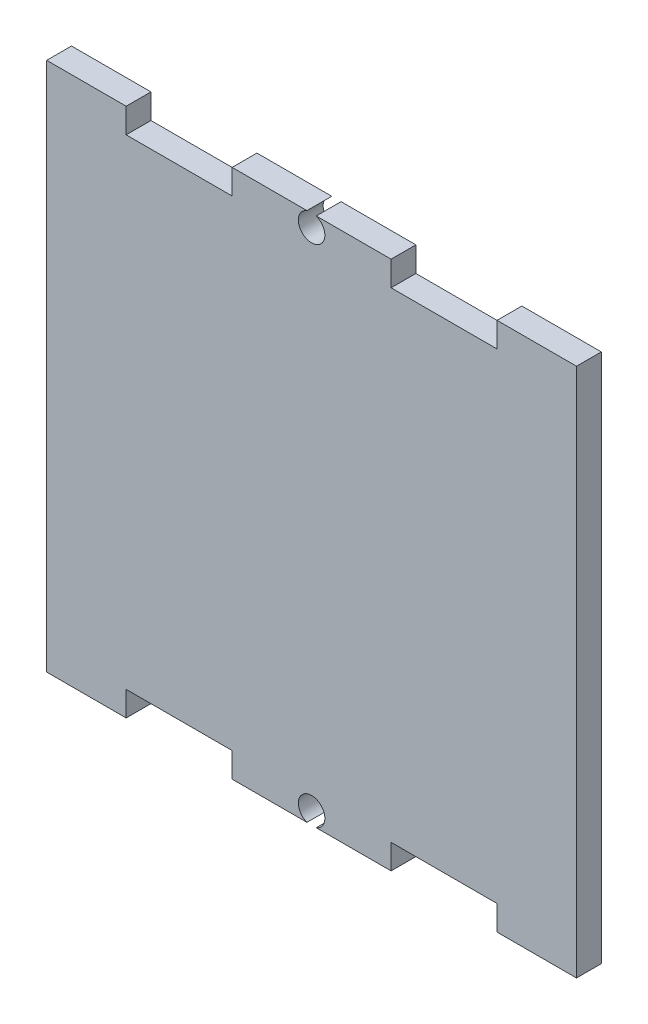
SolidWorks part; units mm, degrees
ref_plane "Front Plane" through (0, 0, 0) normal (0, 0, 1) x (1, 0, 0)
ref_plane "Top Plane" through (0, 0, 0) normal (0, 1, 0) x (1, 0, 0)
ref_plane "Right Plane" through (0, 0, 0) normal (1, 0, 0) x (0, 0, -1)
sketch "Sketch1" plane through (0, 0, 0) normal (0, 0, 1) x (1, 0, 0)
  line L1 (-31.75, -31.75) -> (31.75, -31.75)
  line L2 (-31.75, -31.75) -> (-31.75, 31.75)
  line L3 (-31.75, 31.75) -> (31.75, 31.75)
  line L4 (31.75, -31.75) -> (31.75, 31.75)
  line L5 (-31.75, -31.75) -> (31.75, 31.75) construction
  line L6 (-31.75, 31.75) -> (31.75, -31.75) construction
  point P0 (0, 0)
  dimension "D1" = 63.5
  dimension "D2" = 63.5
extrude "Boss-Extrude1" add sketch "Sketch1" along normal blind 2.9718
sketch "Sketch2" plane through (0, 0, 2.9718) normal (0, 0, 1) x (1, 0, 0)
  line L0 (-31.75, -31.75) -> (31.75, -31.75) construction
  line L1 (9.525, -31.75) -> (9.525, -28.7782)
  line L2 (-22.225, -31.75) -> (-9.525, -31.75)
  line L3 (-22.225, -31.75) -> (-22.225, -28.7782)
  line L4 (-22.225, -28.7782) -> (-9.525, -28.7782)
  line L5 (-9.525, -31.75) -> (-9.525, -28.7782)
  line L6 (9.525, -31.75) -> (22.225, -31.75)
  line L7 (22.225, -31.75) -> (22.225, -28.7782)
  line L8 (9.525, -28.7782) -> (22.225, -28.7782)
  line L9 (-22.225, -31.75) -> (9.525, -31.75) construction
  line L10 (0, 0) -> (36.5705, 0) construction
  line L11 (-22.225, 31.75) -> (9.525, 31.75) construction
  line L12 (9.525, 28.7782) -> (22.225, 28.7782)
  line L13 (22.225, 31.75) -> (22.225, 28.7782)
  line L14 (9.525, 31.75) -> (22.225, 31.75)
  line L15 (-9.525, 31.75) -> (-9.525, 28.7782)
  line L16 (-22.225, 28.7782) -> (-9.525, 28.7782)
  line L17 (-22.225, 31.75) -> (-22.225, 28.7782)
  line L18 (-22.225, 31.75) -> (-9.525, 31.75)
  line L19 (9.525, 31.75) -> (9.525, 28.7782)
  circle A0 centre (0, -30.2641) radius 1.5875
  circle A1 centre (0, 30.2641) radius 1.5875
  point P9 (-15.875, -31.75)
  point P28 (-15.875, 31.75)
  dimension "D1" = 3.175
  dimension "D2" = 1.4859
  dimension "D3" = 2.9718
  dimension "D4" = 12.7
  dimension "D5" = 15.875
  dimension "D6" = 31.75
extrude "Cut-Extrude1" cut sketch "Sketch2" against normal through all
